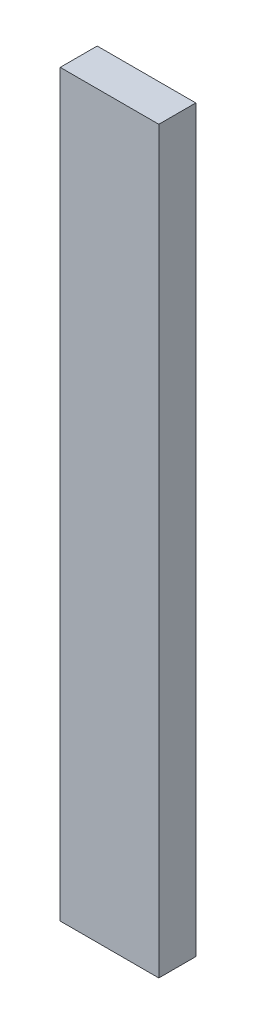
SolidWorks part; units mm, degrees
ref_plane "Front Plane" through (0, 0, 0) normal (0, 0, 1) x (1, 0, 0)
ref_plane "Top Plane" through (0, 0, 0) normal (0, 1, 0) x (1, 0, 0)
ref_plane "Right Plane" through (0, 0, 0) normal (1, 0, 0) x (0, 0, -1)
sketch "Sketch1" plane through (0, 0, 0) normal (0, 0, 1) x (1, 0, 0)
  line L1 (-25.4, -190.5) -> (25.4, -190.5)
  line L2 (-25.4, -190.5) -> (-25.4, 190.5)
  line L3 (-25.4, 190.5) -> (25.4, 190.5)
  line L4 (25.4, -190.5) -> (25.4, 190.5)
  line L5 (-25.4, -190.5) -> (25.4, 190.5) construction
  line L6 (-25.4, 190.5) -> (25.4, -190.5) construction
  point P0 (0, 0)
  dimension "D1" = 381
  dimension "D2" = 50.8
extrude "Boss-Extrude1" add sketch "Sketch1" along normal blind 19.05
